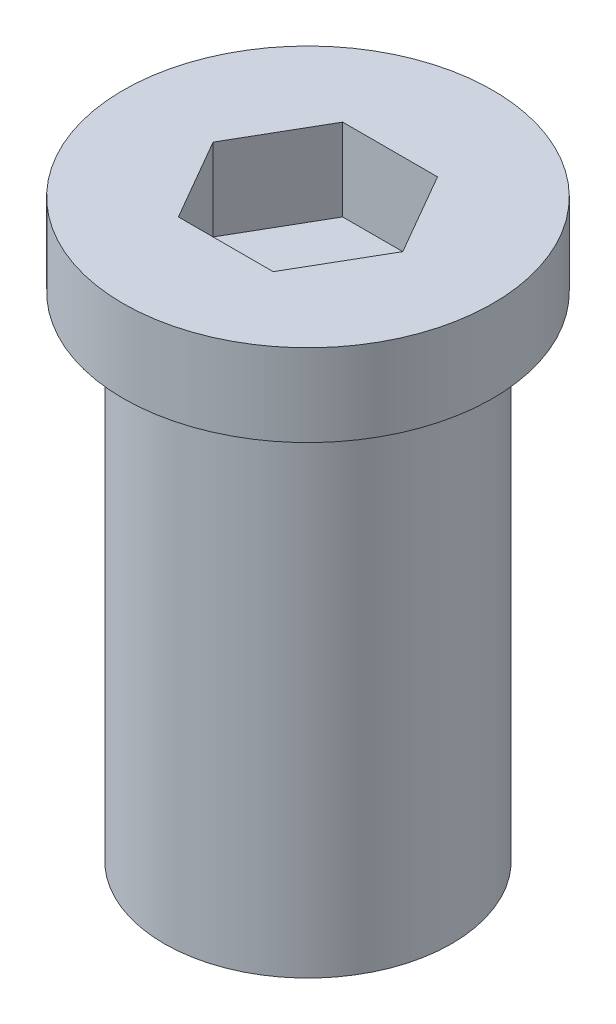
SolidWorks part; units mm, degrees
ref_plane "Front Plane" through (0, 0, 0) normal (0, 0, 1) x (1, 0, 0)
ref_plane "Top Plane" through (0, 0, 0) normal (0, 1, 0) x (1, 0, 0)
ref_plane "Right Plane" through (0, 0, 0) normal (1, 0, 0) x (0, 0, -1)
sketch "Sketch1" plane through (0, 0, 0) normal (0, 1, 0) x (1, 0, 0)
  circle A0 centre (0, 0) radius 1.75
  dimension "D1" = 3.5
extrude "Boss-Extrude1" add sketch "Sketch1" along normal mid plane 6
sketch "Sketch2" plane through (0, 3, 0) normal (0, 1, 0) x (1, 0, 0)
  circle A0 centre (0, 0) radius 2.25
  dimension "D1" = 4.5
extrude "Boss-Extrude2" add sketch "Sketch2" along normal blind 1
sketch "Sketch3" plane through (0, 4, 0) normal (0, 1, 0) x (1, 0, 0)
  line L0 (1.1547, 0) -> (0.5774, 1)
  line L1 (0.5774, 1) -> (-0.5774, 1)
  line L2 (-0.5774, 1) -> (-1.1547, 0)
  line L3 (-1.1547, 0) -> (-0.5774, -1)
  line L4 (-0.5774, -1) -> (0.5774, -1)
  line L5 (0.5774, -1) -> (1.1547, 0)
  circle A0 centre (0, 0) radius 1 construction
  dimension "D1" = 1.1547
  dimension "D7" = 2
  dimension "D2" = 1.1547
  dimension "D3" = 1
  dimension "D4" = 1.1547
  dimension "D5" = 1.1547
  dimension "D6" = 1
extrude "Cut-Extrude1" cut sketch "Sketch3" against normal blind 1
